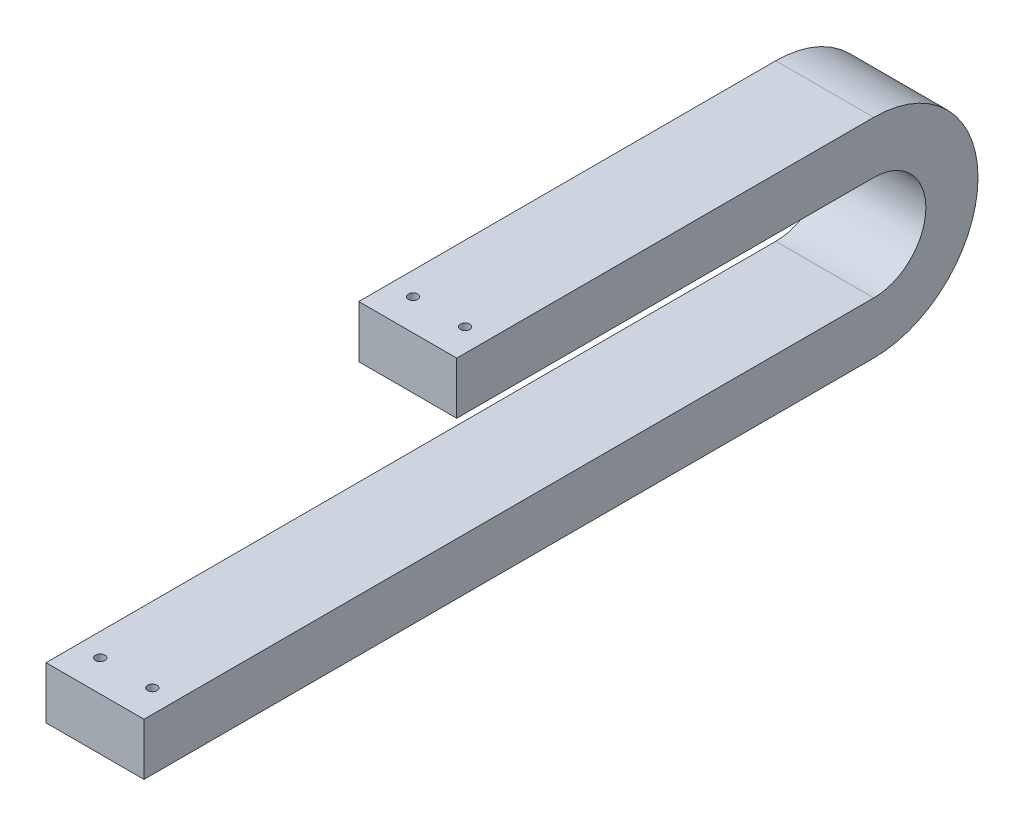
SolidWorks part; units mm, degrees
ref_plane "前视基准面" through (0, 0, 0) normal (0, 0, 1) x (1, 0, 0)
ref_plane "上视基准面" through (0, 0, 0) normal (0, 1, 0) x (1, 0, 0)
ref_plane "右视基准面" through (0, 0, 0) normal (1, 0, 0) x (0, 0, -1)
sketch "草图1" plane through (0, 0, 0) normal (1, 0, 0) x (0, 0, -1)
  line L0 (0, 0) -> (350, 0)
  line L1 (0, 0) -> (0, -25)
  line L2 (0, -25) -> (350, -25)
  line L3 (150, 75) -> (150, 50)
  line L4 (350, 50) -> (150, 50)
  line L5 (350, 75) -> (150, 75)
  arc A0 (350, 0) -> (350, 50) centre (350, 25) ccw
  arc A1 (350, -25) -> (350, 75) centre (350, 25) ccw
  dimension "D1" = 25
  dimension "D2" = 350
  dimension "D3" = 350
  dimension "D4" = 25
  dimension "D5" = 200
extrude "凸台-拉伸1" add sketch "草图1" along normal blind 47
sketch "草图2" plane through (0, 0, 0) normal (0, 1, 0) x (1, 0, 0)
  line L0 (0, 350) -> (0, 0) construction
  line L1 (47, 0) -> (0, 0) construction
  circle A0 centre (36, 15) radius 2.25
  circle A1 centre (11, 15) radius 2.25
  dimension "D1" = 25
  dimension "D2" = 4.5
  dimension "D3" = 4.5
  dimension "D4" = 11
  dimension "D5" = 15
  dimension "D6" = 15
extrude "切除-拉伸1" cut sketch "草图2" against normal blind 90
sketch "草图3" plane through (0, 75, 0) normal (0, 1, 0) x (1, 0, 0)
  line L0 (0, 350) -> (0, 150) construction
  line L1 (47, 150) -> (0, 150) construction
  circle A0 centre (11, 165) radius 2.25
  circle A1 centre (36, 165) radius 2.25
  dimension "D1" = 4.5
  dimension "D2" = 4.5
  dimension "D3" = 25
  dimension "D4" = 11
  dimension "D6" = 15
  dimension "D5" = 15
extrude "切除-拉伸2" cut sketch "草图3" against normal blind 40
